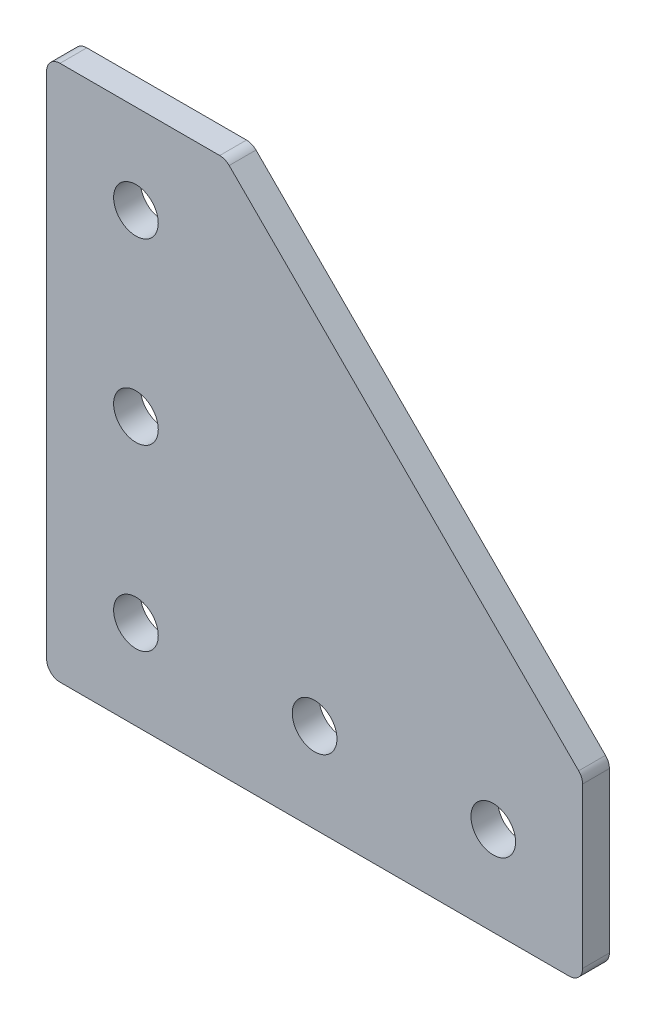
SolidWorks part; units mm, degrees
ref_plane "Front Plane" through (0, 0, 0) normal (0, 0, 1) x (1, 0, 0)
ref_plane "Top Plane" through (0, 0, 0) normal (0, 1, 0) x (1, 0, 0)
ref_plane "Right Plane" through (0, 0, 0) normal (1, 0, 0) x (0, 0, -1)
sketch "Sketch1" plane through (0, 0, 0) normal (0, 0, 1) x (1, 0, 0)
  line L0 (1.5, 60) -> (19.3787, 60)
  line L1 (1.5, 0) -> (58.5, 0)
  line L2 (0, 1.5) -> (0, 58.5)
  line L3 (0, 60) -> (60, 60) construction
  line L4 (60, 0) -> (60, 60) construction
  line L5 (20.4393, 59.5607) -> (59.5607, 20.4393)
  line L6 (60, 19.3787) -> (60, 1.5)
  arc A0 (60, 19.3787) -> (59.5607, 20.4393) centre (58.5, 19.3787) ccw
  arc A1 (58.5, 0) -> (60, 1.5) centre (58.5, 1.5) ccw
  arc A2 (0, 1.5) -> (1.5, 0) centre (1.5, 1.5) ccw
  arc A3 (1.5, 60) -> (0, 58.5) centre (1.5, 58.5) ccw
  arc A4 (19.3787, 60) -> (20.4393, 59.5607) centre (19.3787, 58.5) cw
  point P9 (60, 20)
  point P15 (0, 0)
  point P21 (20, 60)
  dimension "D5" = 1.5
  dimension "D1" = 60
  dimension "D2" = 60
  dimension "D3" = 20
  dimension "D4" = 20
extrude "Boss-Extrude1" add sketch "Sketch1" against normal blind 3
sketch "Sketch2" plane through (0, 0, 0) normal (0, 0, 1) x (1, 0, 0)
  line L0 (0, 58.5) -> (0, 1.5) construction
  line L1 (1.5, 0) -> (58.5, 0) construction
  line L2 (10, 50) -> (10, 30) construction
  line L3 (10, 30) -> (10, 10) construction
  line L4 (10, 10) -> (30, 10) construction
  line L5 (30, 10) -> (50, 10) construction
  circle A0 centre (10, 10) radius 2.5
  circle A1 centre (30, 10) radius 2.5
  circle A2 centre (50, 10) radius 2.5
  circle A3 centre (10, 30) radius 2.5
  circle A4 centre (10, 50) radius 2.5
  dimension "D3" = 5
  dimension "D1" = 10
  dimension "D2" = 10
  dimension "D6" = 20
  dimension "D7" = 20
  dimension "D4" = 3
  dimension "D5" = 3
extrude "Cut-Extrude1" cut sketch "Sketch2" against normal blind 3 contours A4
